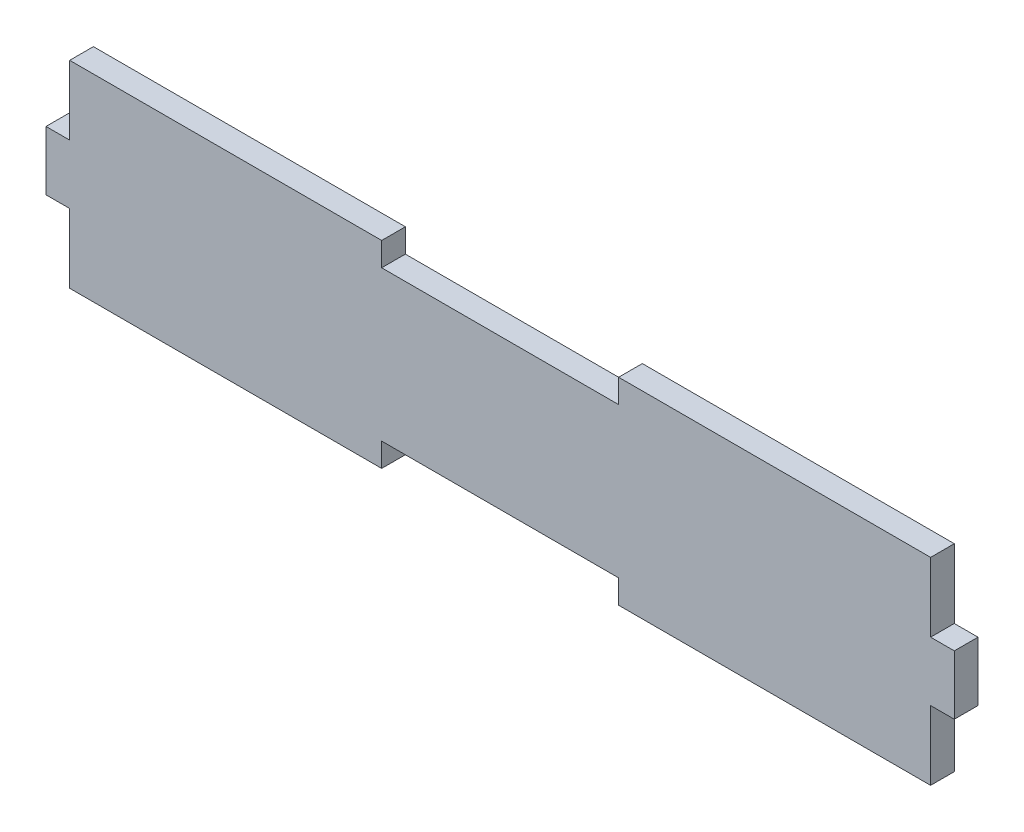
SolidWorks part; units mm, degrees
material "6061-T6 (SS)"
ref_plane "Alzado" through (0, 0, 0) normal (0, 0, 1) x (1, 0, 0)
ref_plane "Planta" through (0, 0, 0) normal (0, 1, 0) x (1, 0, 0)
ref_plane "Vista lateral" through (0, 0, 0) normal (1, 0, 0) x (0, 0, -1)
sketch "Croquis1" plane through (0, 0, 0) normal (0, 0, 1) x (1, 0, 0)
  line L0 (-30, 19) -> (-30, 25)
  line L1 (-30, -19) -> (30, -19)
  line L2 (-109, -25) -> (-109, -7.5)
  line L3 (-30, 19) -> (30, 19)
  line L4 (109, -25) -> (109, -7.5)
  line L5 (30, 25) -> (109, 25)
  line L6 (30, 19) -> (30, 25)
  line L7 (-30, 25) -> (-109, 25)
  line L8 (-115, 0) -> (115, 0) construction
  line L9 (0, -19) -> (0, 19) construction
  line L10 (30, -25) -> (109, -25)
  line L11 (30, -19) -> (30, -25)
  line L12 (-30, -19) -> (-30, -25)
  line L13 (-30, -25) -> (-109, -25)
  line L14 (-109, 7.5) -> (-109, 25)
  line L15 (-109, 7.5) -> (-115, 7.5)
  line L17 (-109, -7.5) -> (-115, -7.5)
  line L18 (-115, 7.5) -> (-115, -7.5)
  line L19 (109, -7.5) -> (115, -7.5)
  line L20 (115, 7.5) -> (115, -7.5)
  line L21 (109, 7.5) -> (115, 7.5)
  line L22 (109, 7.5) -> (109, 25)
  point P0 (0, 0)
  point P24 (0, 0)
  point P32 (0, 0)
  dimension "D1" = 60
  dimension "D2" = 15
  dimension "D3" = 6
  dimension "D4" = 50
  dimension "D5" = 6
  dimension "D6" = 230
extrude "Saliente-Extruir1" add sketch "Croquis1" along normal blind 6
